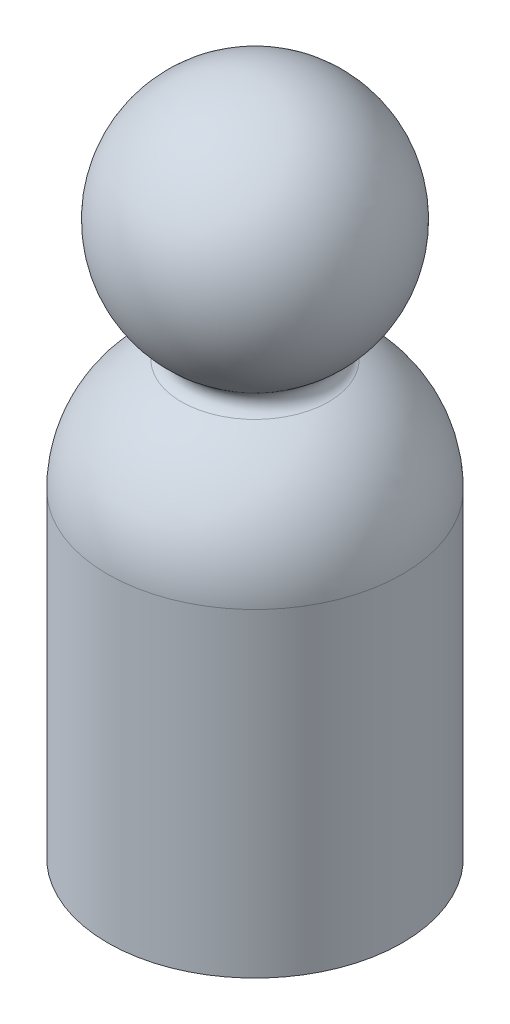
SolidWorks part; units mm, degrees
material "Mahogany"
ref_plane "Front" through (0, 0, 0) normal (0, 0, 1) x (1, 0, 0)
ref_plane "Top" through (0, 0, 0) normal (0, 1, 0) x (1, 0, 0)
ref_plane "Right" through (0, 0, 0) normal (1, 0, 0) x (0, 0, -1)
sketch "Sketch1" plane through (0, 0, 0) normal (0, 0, 1) x (1, 0, 0)
  line L0 (0, 0) -> (12, 0)
  line L1 (12, 0) -> (12, 26)
  line L2 (0, 55.0282) -> (0, 0) construction
  line L3 (0, 0) -> (0, 55.0282) construction
  line L4 (0, 0) -> (0, 55.0282)
  arc A0 (12, 26) -> (6, 35.1652) centre (2, 26) ccw
  arc A1 (6, 35.1652) -> (5.8182, 36.895) centre (6.4, 36.0817) cw
  arc A2 (5.8182, 36.895) -> (0, 55.0282) centre (0, 45.0282) ccw
  dimension "D3" = 10
  dimension "D5" = 1
  dimension "D6" = 10
  dimension "D1" = 24
  dimension "D2" = 26
  dimension "D4" = 12.8
revolve "Revolve1" add sketch "Sketch1" angle 360 about L4
